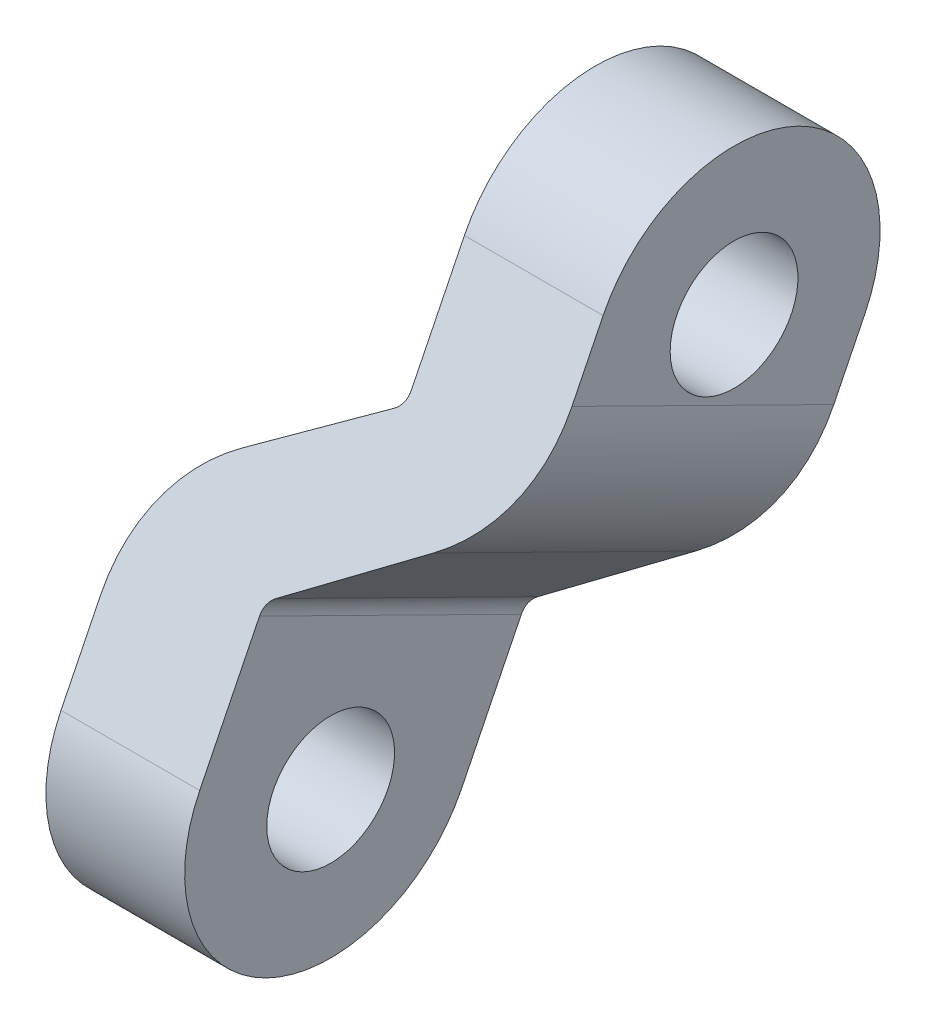
SolidWorks part; units mm, degrees
ref_plane "Front Plane" through (0, 0, 0) normal (0, 0, 1) x (1, 0, 0)
ref_plane "Top Plane" through (0, 0, 0) normal (0, 1, 0) x (1, 0, 0)
ref_plane "Right Plane" through (0, 0, 0) normal (1, 0, 0) x (0, 0, -1)
ref_plane "Plane1" through (-27.4808, 0, 0) normal (1, 0, 0) x (0, 0, -1)
sketch "Sketch1" plane through (-27.4808, 0, 0) normal (1, 0, 0) x (0, 0, -1)
  line L0 (81.9633, -40.97) -> (76.4133, -52.211)
  line L1 (83.5867, -55.7526) -> (89.1367, -44.5116)
  arc A0 (76.4133, -52.211) -> (83.5867, -55.7526) centre (80, -53.9818) ccw
  arc A1 (89.1367, -44.5116) -> (81.9633, -40.97) centre (85.55, -42.7408) ccw
extrude "Boss-Extrude1" add sketch "Sketch1" against normal blind 9.3
sketch "Sketch2" plane through (0, -44.1077, -89.3361) normal (0, -0.4427, -0.8967) x (-1, 0, 0)
  line L0 (31.2808, 3.9482) -> (31.2808, -4.0497)
  line L1 (31.2808, -4.0497) -> (36.7808, -7.9743)
  line L2 (36.7808, -7.9743) -> (36.7808, 3.9482)
  line L3 (36.7808, 3.9482) -> (31.2808, 3.9482)
  line L5 (27.4808, -12.987) -> (27.4808, -0.4505) construction
  line L6 (36.7808, -12.987) -> (36.7808, -0.4505) construction
  dimension "D1" = 11.9225
  dimension "D2" = 3.8
extrude "Cut-Extrude1" cut sketch "Sketch2" against normal through all
sketch "Sketch3" plane through (0, -44.1077, -89.3361) normal (0, -0.4427, -0.8967) x (-1, 0, 0)
  line L0 (32.9808, -17.8885) -> (32.9808, -8.987)
  line L1 (32.9808, -8.987) -> (27.4808, -4.8885)
  line L2 (27.4808, -4.8885) -> (27.4808, -17.8885)
  line L3 (27.4808, -17.8885) -> (32.9808, -17.8885)
  line L4 (36.7808, -12.987) -> (36.7808, -7.9743) construction
  line L5 (27.4808, -12.987) -> (27.4808, -0.4505) construction
  dimension "D1" = 13
  dimension "D2" = 8.9015
  dimension "D3" = 3.8
extrude "Cut-Extrude2" cut sketch "Sketch3" against normal through all
hole_wizard "Hole1" positions "Sketch5" profile "Sketch4" legacy end condition up to next
sketch "Sketch5" plane through (-36.7808, 0, 0) normal (-1, 0, 0) x (0, 0, 1)
  point P0 (-80, -53.9818)
sketch "Sketch4" plane through (-36.7808, -53.9818, -80) normal (0, 1, 0) x (0, 0, 1)
  line L0 (0, 0) -> (0, 3.8)
  line L1 (0, 3.8) -> (1.75, 3.8)
  line L2 (1.75, 3.8) -> (1.75, 0)
  line L3 (1.75, 0) -> (0, 0)
  line L4 (0, 110) -> (0, -10) construction
  dimension "Diameter" = 3.5
  dimension "Depth" = 3.8
hole_wizard "Hole2" positions "Sketch7" profile "Sketch6" legacy end condition through all
sketch "Sketch7" plane through (-31.2808, 0, 0) normal (-1, 0, 0) x (0, 0, 1)
  point P0 (-85.55, -42.7408)
sketch "Sketch6" plane through (-31.2808, -42.7408, -85.55) normal (0, 1, 0) x (0, 0, 1)
  line L0 (0, 0) -> (0, 3.8)
  line L1 (0, 3.8) -> (1.75, 3.8)
  line L2 (1.75, 3.8) -> (1.75, 0)
  line L3 (1.75, 0) -> (0, 0)
  line L4 (0, 110) -> (0, -10) construction
  dimension "Diameter" = 3.5
  dimension "Depth" = 3.8
fillet "Fillet1" radius 0.6 2 edges at (-32.9808, -50.3951, -81.7708) (-31.2808, -45.968, -83.9566)
fillet "Fillet2" radius 5 2 edges at (-27.4808, -46.7202, -83.5853) (-36.7808, -49.4871, -82.2192)
